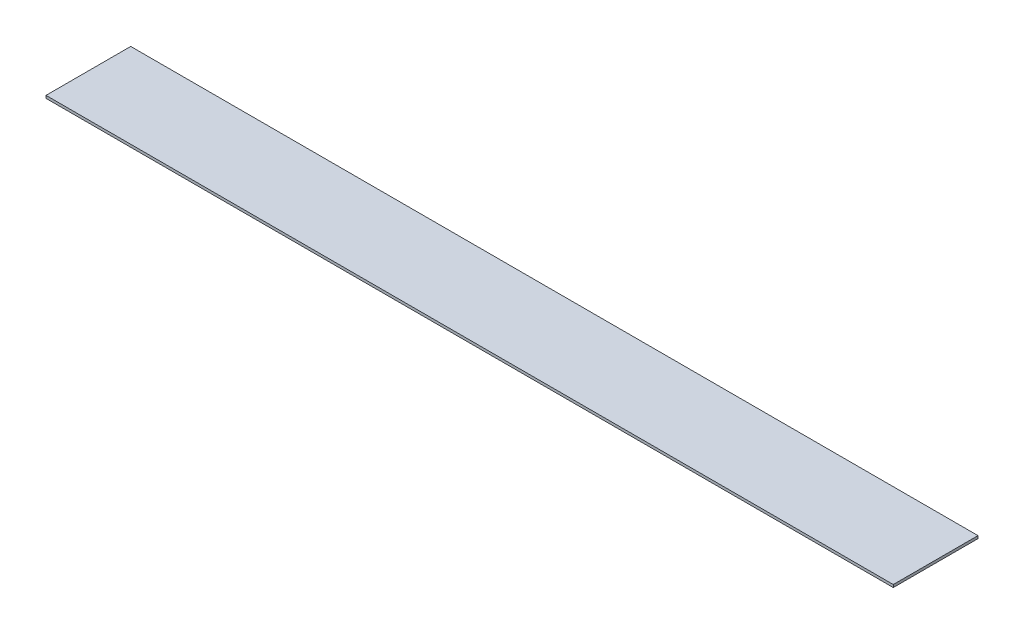
SolidWorks part; units mm, degrees
material "Nylon 101"
ref_plane "Front Plane" through (0, 0, 0) normal (0, 0, 1) x (1, 0, 0)
ref_plane "Top Plane" through (0, 0, 0) normal (0, 1, 0) x (1, 0, 0)
ref_plane "Right Plane" through (0, 0, 0) normal (1, 0, 0) x (0, 0, -1)
sketch "Sketch1" plane through (0, 0, 0) normal (0, -1, 0) x (1, 0, 0)
  line L2 (0, 0) -> (508, 0)
  line L3 (0, 0) -> (0, 50.8)
  line L4 (0, 50.8) -> (508, 50.8)
  line L5 (508, 0) -> (508, 50.8)
  point P4 (0, 0)
  dimension "D2" = 508
  dimension "D1" = 50.8
extrude "Boss-Extrude1" add sketch "Sketch1" along normal blind 1.5875
